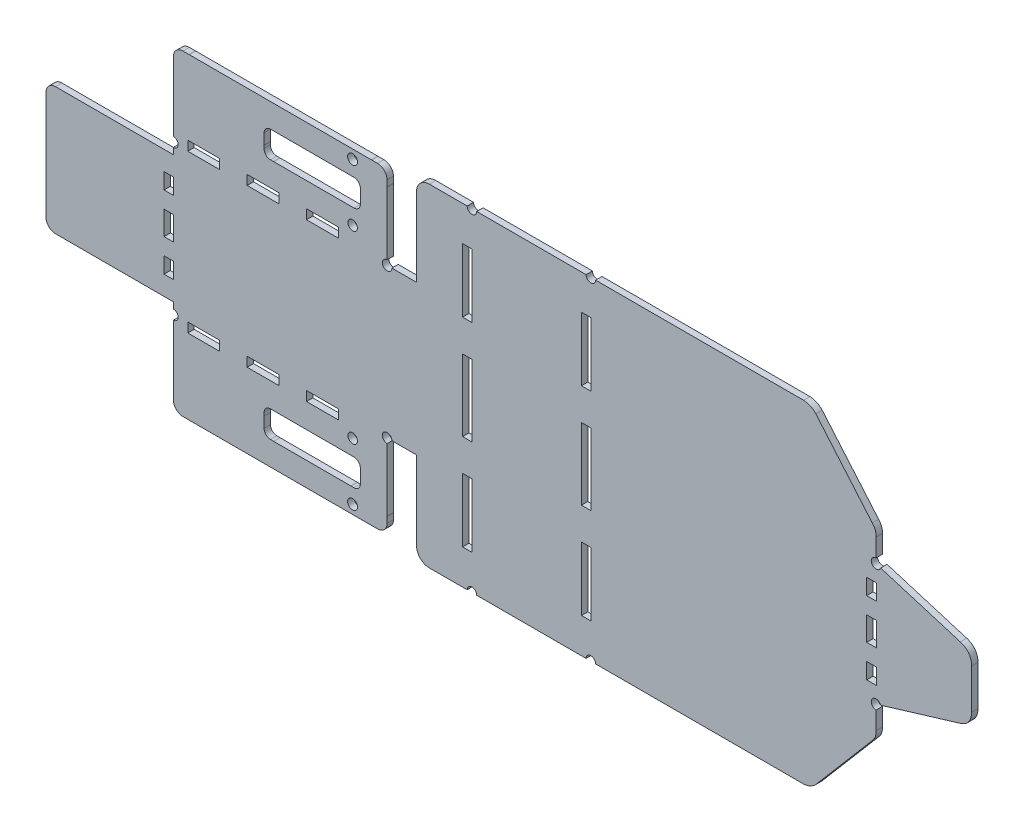
SolidWorks part; units mm, degrees
ref_plane "Plano frontal" through (0, 0, 0) normal (0, 0, 1) x (1, 0, 0)
ref_plane "Plano superior" through (0, 0, 0) normal (0, 1, 0) x (1, 0, 0)
ref_plane "Plano direito" through (0, 0, 0) normal (1, 0, 0) x (0, 0, -1)
sketch "Model" plane through (0, 0, 0) normal (0, 0, 1) x (1, 0, 0)
  line L0 (-37.9138, 33.827) -> (-37.9138, 63.827)
  line L1 (64.1787, 98.5214) -> (64.3494, 98.5185)
  line L2 (133.1985, 47.5895) -> (133.1985, 37.5895)
  line L3 (131.6352, -3.3472) -> (97.3086, -3.3472)
  line L4 (199.9402, -3.3472) -> (134.6352, -3.3472)
  line L5 (221.4884, 19.2431) -> (203.7468, -1.5891)
  line L6 (222.6818, 28.157) -> (222.6818, 22.485)
  line L7 (249.1319, 37.7513) -> (224.1174, 30.1707)
  line L8 (2.0862, 28.827) -> (-32.9138, 28.827)
  line L9 (2.0862, 26.8558) -> (2.0862, 28.827)
  line L10 (2.0862, 4.1326) -> (2.0862, 23.8558)
  line L11 (7.0862, -0.8674) -> (6.9155, -0.8645)
  line L12 (64.1787, -0.8674) -> (7.0862, -0.8674)
  line L13 (69.1787, 4.1326) -> (69.1757, 3.9619)
  line L14 (69.1787, 23.8558) -> (69.1787, 4.1326)
  line L15 (78.4133, 25.3558) -> (70.6787, 25.3558)
  line L16 (78.4133, 1.6528) -> (78.4133, 25.3558)
  line L17 (94.3086, -3.3472) -> (83.4133, -3.3472)
  line L18 (95.8719, 7.5895) -> (92.8719, 7.5895)
  line L19 (95.8719, 27.5895) -> (95.8719, 7.5895)
  line L20 (92.8719, 27.5895) -> (95.8719, 27.5895)
  line L21 (92.8719, 7.5895) -> (92.8719, 27.5895)
  line L22 (133.1985, 7.5895) -> (130.1985, 7.5895)
  line L23 (133.1985, 27.5895) -> (133.1985, 7.5895)
  line L24 (130.1985, 27.5895) -> (133.1985, 27.5895)
  line L25 (130.1985, 7.5895) -> (130.1985, 27.5895)
  line L26 (35.2343, 22.6182) -> (25.2343, 22.6182)
  line L27 (35.2343, 25.6182) -> (35.2343, 22.6182)
  line L28 (25.2343, 25.6182) -> (35.2343, 25.6182)
  line L29 (25.2343, 22.6182) -> (25.2343, 25.6182)
  line L30 (16.5992, 22.6182) -> (6.5992, 22.6182)
  line L31 (16.5992, 25.6182) -> (16.5992, 22.6182)
  line L32 (6.5992, 25.6182) -> (16.5992, 25.6182)
  line L33 (6.5992, 22.6182) -> (6.5992, 25.6182)
  line L34 (43.8695, 25.6182) -> (43.8695, 22.6182)
  line L35 (53.8695, 25.6182) -> (43.8695, 25.6182)
  line L36 (53.8695, 22.6182) -> (53.8695, 25.6182)
  line L37 (43.8695, 22.6182) -> (53.8695, 22.6182)
  line L38 (133.1985, 37.5895) -> (130.1985, 37.5895)
  line L39 (95.8719, 37.5895) -> (92.8719, 37.5895)
  line L40 (2.1495, 45.0895) -> (-0.8505, 45.0895)
  line L41 (2.1495, 34.8818) -> (-0.8505, 34.8818)
  line L42 (2.1495, 39.8818) -> (2.1495, 34.8818)
  line L43 (-0.8505, 39.8818) -> (2.1495, 39.8818)
  line L44 (-0.8505, 34.8818) -> (-0.8505, 39.8818)
  line L45 (222.7451, 45.0895) -> (219.7451, 45.0895)
  line L46 (222.7451, 34.8818) -> (219.7451, 34.8818)
  line L47 (222.7451, 39.8818) -> (222.7451, 34.8818)
  line L48 (219.7451, 39.8818) -> (222.7451, 39.8818)
  line L49 (219.7451, 34.8818) -> (219.7451, 39.8818)
  line L50 (33.5546, 14.9679) -> (57.7758, 14.9679)
  line L51 (33.4522, 14.9662) -> (33.5546, 14.9679)
  line L52 (30.5546, 11.9679) -> (30.5564, 12.0704)
  line L53 (30.5546, 9.6328) -> (30.5546, 11.9679)
  line L54 (57.7758, 6.6328) -> (33.5546, 6.6328)
  line L55 (57.8782, 6.6346) -> (57.7758, 6.6328)
  line L56 (60.7758, 9.6328) -> (60.774, 9.5304)
  line L57 (60.7758, 11.9679) -> (60.7758, 9.6328)
  line L58 (82.4133, -3.3472) -> (83.4133, -3.3472)
  line L59 (78.4133, 1.6528) -> (78.4133, 0.6528)
  line L60 (-34.9138, 28.827) -> (-32.9138, 28.827)
  line L61 (-37.9138, 33.827) -> (-37.9138, 31.827)
  line L62 (32.5414, 14.9662) -> (33.4522, 14.9662)
  line L63 (30.5564, 12.0704) -> (30.5417, 12.932)
  line L64 (58.7758, 14.9679) -> (57.7758, 14.9679)
  line L65 (60.7758, 11.9679) -> (60.7758, 12.9679)
  line L66 (60.774, 8.6346) -> (60.774, 9.5304)
  line L67 (57.8782, 6.6346) -> (58.774, 6.6346)
  line L68 (32.5392, 6.6406) -> (33.5546, 6.6328)
  line L69 (30.5546, 9.6328) -> (30.5546, 8.6406)
  line L70 (69.1757, 2.1355) -> (69.1757, 3.9619)
  line L71 (64.3494, -0.8645) -> (66.1757, -0.8645)
  line L72 (2.0892, 3.9619) -> (2.0862, 4.1326)
  line L73 (5.0892, -0.8645) -> (6.9155, -0.8645)
  line L74 (2.0892, 3.9619) -> (2.0892, 2.1355)
  line L75 (64.1787, -0.8674) -> (64.3494, -0.8645)
  line L362 (2.0892, 93.6922) -> (2.0892, 95.5185)
  line L363 (5.0892, 98.5185) -> (6.9155, 98.5185)
  line L364 (2.0892, 93.6922) -> (2.0862, 93.5214)
  line L365 (64.3494, 98.5185) -> (66.1757, 98.5185)
  line L366 (69.1757, 95.5185) -> (69.1757, 93.6922)
  line L367 (30.5546, 88.0212) -> (30.5546, 89.0135)
  line L368 (32.5392, 91.0134) -> (33.5546, 91.0212)
  line L369 (57.8782, 91.0195) -> (58.774, 91.0195)
  line L370 (60.774, 89.0195) -> (60.774, 88.1236)
  line L371 (60.7758, 85.6861) -> (60.7758, 84.6861)
  line L372 (58.7758, 82.6861) -> (57.7758, 82.6861)
  line L373 (30.5564, 85.5837) -> (30.5417, 84.722)
  line L374 (32.5414, 82.6879) -> (33.4522, 82.6879)
  line L375 (-37.9138, 63.827) -> (-37.9138, 65.827)
  line L376 (-34.9138, 68.827) -> (-32.9138, 68.827)
  line L377 (78.4133, 96.0013) -> (78.4133, 97.0013)
  line L378 (82.4133, 101.0013) -> (83.4133, 101.0013)
  line L2722 (60.7758, 85.6861) -> (60.7758, 88.0212)
  line L2723 (60.7758, 88.0212) -> (60.774, 88.1236)
  line L2768 (57.8782, 91.0195) -> (57.7758, 91.0212)
  line L2769 (57.7758, 91.0212) -> (33.5546, 91.0212)
  line L2816 (30.5546, 88.0212) -> (30.5546, 85.6861)
  line L2817 (30.5546, 85.6861) -> (30.5564, 85.5837)
  line L2862 (33.4522, 82.6879) -> (33.5546, 82.6861)
  line L2863 (33.5546, 82.6861) -> (57.7758, 82.6861)
  line L10879 (219.7451, 62.7722) -> (219.7451, 57.7722)
  line L10880 (219.7451, 57.7722) -> (222.7451, 57.7722)
  line L10881 (222.7451, 57.7722) -> (222.7451, 62.7722)
  line L10882 (222.7451, 62.7722) -> (219.7451, 62.7722)
  line L10883 (219.7451, 52.5646) -> (219.7451, 45.0895)
  line L10885 (222.7451, 45.0895) -> (222.7451, 52.5646)
  line L10886 (222.7451, 52.5646) -> (219.7451, 52.5646)
  line L10892 (-0.8505, 62.7722) -> (-0.8505, 57.7722)
  line L10893 (-0.8505, 57.7722) -> (2.1495, 57.7722)
  line L10894 (2.1495, 57.7722) -> (2.1495, 62.7722)
  line L10895 (2.1495, 62.7722) -> (-0.8505, 62.7722)
  line L10896 (-0.8505, 52.5646) -> (-0.8505, 45.0895)
  line L10898 (2.1495, 45.0895) -> (2.1495, 52.5646)
  line L10899 (2.1495, 52.5646) -> (-0.8505, 52.5646)
  line L10900 (92.8719, 60.0646) -> (92.8719, 37.5895)
  line L10902 (95.8719, 37.5895) -> (95.8719, 60.0646)
  line L10903 (95.8719, 60.0646) -> (92.8719, 60.0646)
  line L10904 (133.1985, 47.5895) -> (133.1985, 50.0646)
  line L10905 (133.1985, 50.0646) -> (133.1985, 60.0646)
  line L10906 (133.1985, 60.0646) -> (130.1985, 60.0646)
  line L10907 (130.1985, 60.0646) -> (130.1985, 37.5895)
  line L11653 (43.8695, 75.0359) -> (53.8695, 75.0359)
  line L11654 (53.8695, 75.0359) -> (53.8695, 72.0359)
  line L11655 (53.8695, 72.0359) -> (43.8695, 72.0359)
  line L11656 (43.8695, 72.0359) -> (43.8695, 75.0359)
  line L11657 (6.5992, 75.0359) -> (6.5992, 72.0359)
  line L11658 (6.5992, 72.0359) -> (16.5992, 72.0359)
  line L11659 (16.5992, 72.0359) -> (16.5992, 75.0359)
  line L11660 (16.5992, 75.0359) -> (6.5992, 75.0359)
  line L11661 (25.2343, 75.0359) -> (25.2343, 72.0359)
  line L11662 (25.2343, 72.0359) -> (35.2343, 72.0359)
  line L11663 (35.2343, 72.0359) -> (35.2343, 75.0359)
  line L11664 (35.2343, 75.0359) -> (25.2343, 75.0359)
  line L11665 (130.1985, 90.0646) -> (130.1985, 70.0646)
  line L11666 (130.1985, 70.0646) -> (133.1985, 70.0646)
  line L11667 (133.1985, 70.0646) -> (133.1985, 90.0646)
  line L11668 (133.1985, 90.0646) -> (130.1985, 90.0646)
  line L11669 (92.8719, 90.0646) -> (92.8719, 70.0646)
  line L11670 (92.8719, 70.0646) -> (95.8719, 70.0646)
  line L11671 (95.8719, 70.0646) -> (95.8719, 90.0646)
  line L11672 (95.8719, 90.0646) -> (92.8719, 90.0646)
  line L12669 (94.3086, 101.0013) -> (83.4133, 101.0013)
  line L12716 (78.4133, 96.0013) -> (78.4133, 72.2983)
  line L12717 (78.4133, 72.2983) -> (70.6787, 72.2983)
  line L12854 (69.1787, 73.7983) -> (69.1787, 93.5214)
  line L12855 (69.1787, 93.5214) -> (69.1757, 93.6922)
  line L12901 (64.1787, 98.5214) -> (7.0862, 98.5214)
  line L12902 (7.0862, 98.5214) -> (6.9155, 98.5185)
  line L12948 (2.0862, 93.5214) -> (2.0862, 73.7983)
  line L13040 (2.0862, 70.7983) -> (2.0862, 68.827)
  line L13041 (2.0862, 68.827) -> (-32.9138, 68.827)
  line L13088 (-37.9138, 63.827) -> (-37.9138, 48.827)
  line L13952 (252.6818, 42.5364) -> (252.6818, 55.1177)
  line L13990 (249.1319, 59.9028) -> (224.1174, 67.4833)
  line L14118 (222.6818, 69.497) -> (222.6818, 75.1691)
  line L14140 (221.4884, 78.411) -> (203.7468, 99.2431)
  line L14166 (199.9402, 101.0013) -> (134.6352, 101.0013)
  line L14258 (131.6352, 101.0013) -> (97.3086, 101.0013)
  circle A0 centre (58.3264, 95.7208) radius 1.5651
  arc A1 (32.5414, 82.6879) -> (30.5417, 84.722) centre (32.5414, 84.6879) cw
  arc A2 (58.774, 91.0195) -> (60.774, 89.0195) centre (58.774, 89.0195) cw
  arc A3 (60.7758, 84.6861) -> (58.7758, 82.6861) centre (58.7758, 84.6861) cw
  arc A4 (30.5546, 89.0135) -> (32.5392, 91.0134) centre (32.5546, 89.0135) cw
  arc A5 (66.1757, 98.5185) -> (69.1757, 95.5185) centre (66.1757, 95.5185) cw
  arc A6 (2.0892, 95.5185) -> (5.0892, 98.5185) centre (5.0892, 95.5185) cw
  circle A7 centre (58.3649, 77.7865) radius 1.4995
  arc A8 (2.0862, 70.7983) -> (2.0862, 73.7983) centre (2.0862, 72.2983) ccw
  arc A10 (69.1787, 73.7983) -> (70.6787, 72.2983) centre (69.1787, 72.2983) ccw
  arc A11 (-37.9138, 65.827) -> (-34.9138, 68.827) centre (-34.9138, 65.827) cw
  arc A12 (78.4133, 97.0013) -> (82.4133, 101.0013) centre (82.4133, 97.0013) cw
  arc A13 (94.3086, 101.0013) -> (97.3086, 101.0013) centre (95.8086, 101.0013) ccw
  arc A14 (131.6352, 101.0013) -> (134.6352, 101.0013) centre (133.1352, 101.0013) ccw
  arc A15 (222.6818, 69.497) -> (224.1174, 67.4833) centre (222.6818, 67.9785) ccw
  arc A16 (222.6818, 28.157) -> (224.1174, 30.1707) centre (222.6818, 29.6756) cw
  arc A17 (131.6352, -3.3472) -> (134.6352, -3.3472) centre (133.1352, -3.3472) cw
  arc A18 (94.3086, -3.3472) -> (97.3086, -3.3472) centre (95.8086, -3.3472) cw
  arc A19 (78.4133, 0.6528) -> (82.4133, -3.3472) centre (82.4133, 0.6528) ccw
  arc A20 (-37.9138, 31.827) -> (-34.9138, 28.827) centre (-34.9138, 31.827) ccw
  arc A21 (69.1787, 23.8558) -> (70.6787, 25.3558) centre (69.1787, 25.3558) cw
  arc A22 (2.0862, 26.8558) -> (2.0862, 23.8558) centre (2.0862, 25.3558) cw
  circle A23 centre (58.3649, 19.8675) radius 1.4995
  arc A24 (2.0892, 2.1355) -> (5.0892, -0.8645) centre (5.0892, 2.1355) ccw
  arc A25 (66.1757, -0.8645) -> (69.1757, 2.1355) centre (66.1757, 2.1355) ccw
  arc A26 (30.5546, 8.6406) -> (32.5392, 6.6406) centre (32.5546, 8.6406) ccw
  arc A27 (60.7758, 12.9679) -> (58.7758, 14.9679) centre (58.7758, 12.9679) ccw
  arc A28 (58.774, 6.6346) -> (60.774, 8.6346) centre (58.774, 8.6346) ccw
  arc A29 (32.5414, 14.9662) -> (30.5417, 12.932) centre (32.5414, 12.9662) ccw
  circle A30 centre (58.3264, 1.9333) radius 1.5651
  spline S0 degree 2 poles (199.9402, 101.0013) (202.1794, 100.8554) (203.7468, 99.2431) knots 0 0 0 1 1 1
  spline S1 degree 2 poles (221.4884, 78.411) (222.7621, 77.0529) (222.6818, 75.1691) knots 0 0 0 1 1 1
  spline S2 degree 2 poles (249.1319, 59.9028) (252.5815, 58.8528) (252.6818, 55.1177) knots 0 0 0 1 1 1
  spline S3 degree 2 poles (249.1319, 37.7513) (252.5815, 38.8013) (252.6818, 42.5364) knots 0 0 0 1 1 1
  spline S4 degree 2 poles (221.4884, 19.2431) (222.7621, 20.6011) (222.6818, 22.485) knots 0 0 0 1 1 1
  spline S5 degree 2 poles (199.9402, -3.3472) (202.1794, -3.2014) (203.7468, -1.5891) knots 0 0 0 1 1 1
  point P16 (222.7451, 48.827)
  point P17 (219.7451, 48.827)
  point P18 (133.1985, 48.827)
  point P20 (130.1985, 48.827)
  point P21 (95.8719, 48.827)
  point P22 (92.8719, 48.827)
  point P23 (2.1495, 48.827)
  point P24 (-0.8505, 48.827)
  dimension "D1" = 2
  dimension "D2" = 2
  dimension "D3" = 3
  dimension "D4" = 3
  dimension "D5" = 3
  dimension "D6" = 4
extrude "Ressalto-extrusão1" add sketch "Model" along normal blind 2 contours L4 S5 L5 S4 L6 A16 L7 S3 L13952 S2 L13990 A15 L14118 S1 L14140 S0 L14166 A14 L14258 A13 L12669 L378 A12 L377 L12716 L12717 A10 L12854 L12855 L366 A5 L365 L1 L12901 L12902 L363 A6 L362 L364 L12948 A8 L13040 L13041 L376 A11 L375 L0 L61 A20 L60
